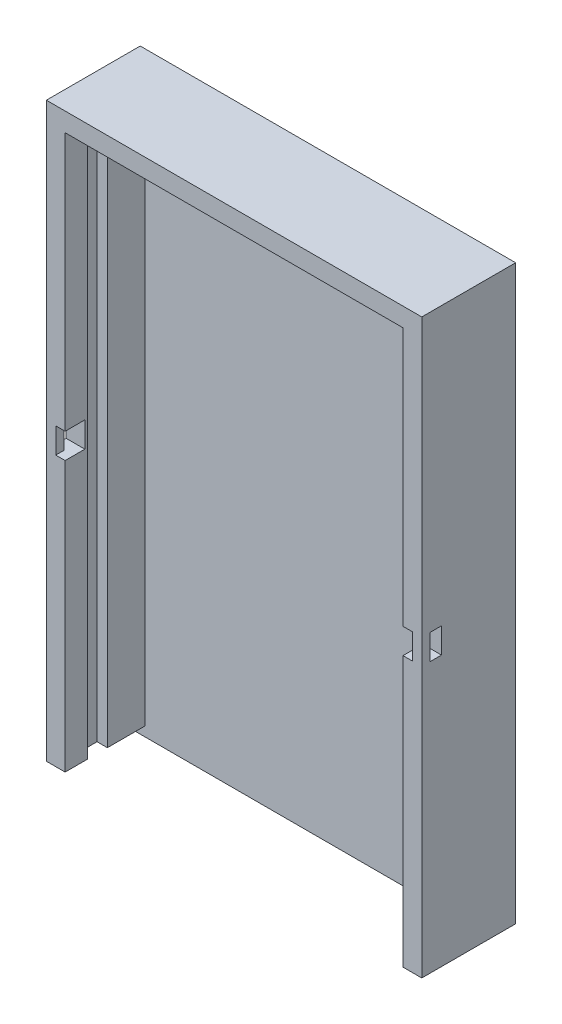
SolidWorks part; units mm, degrees
ref_plane "前视基准面" through (0, 0, 0) normal (0, 0, 1) x (1, 0, 0)
ref_plane "上视基准面" through (0, 0, 0) normal (0, 1, 0) x (1, 0, 0)
ref_plane "右视基准面" through (0, 0, 0) normal (1, 0, 0) x (0, 0, -1)
sketch "草图1" plane through (0, 0, 0) normal (0, 0, 1) x (1, 0, 0)
  line L1 (-20, 31) -> (20, 31)
  line L2 (-20, 31) -> (-20, -31)
  line L3 (-20, -31) -> (20, -31)
  line L4 (20, 31) -> (20, -31)
  line L5 (-20, 31) -> (20, -31) construction
  line L6 (-20, -31) -> (20, 31) construction
  point P0 (0, 0)
  dimension "D1" = 40
  dimension "D2" = 62
extrude "凸台-拉伸1" add sketch "草图1" along normal blind 10 contours L2 L1 L4 L3
sketch "草图2" plane through (0, 0, 10) normal (0, 0, 1) x (1, 0, 0)
  line L12 (18, -29) -> (18, 29)
  line L13 (18, 29) -> (-18, 29)
  line L14 (-18, 29) -> (-18, -29)
  line L15 (-18, -29) -> (18, -29)
  line L16 (18, -29) -> (18, 29)
  line L17 (18, 29) -> (-18, 29)
  line L18 (-18, 29) -> (-18, -29)
  line L19 (-18, -29) -> (18, -29)
  dimension "D1" = 2
extrude "切除-拉伸1" cut sketch "草图2" against normal blind 8.5
sketch "草图4" plane through (0, -31, 0) normal (0, -1, 0) x (1, 0, 0)
  line L0 (-20, 10) -> (20, 10) construction
  line L1 (-18, 10) -> (18, 10)
  line L2 (-18, 10) -> (-18, 1.5)
  line L3 (-18, 1.5) -> (18, 1.5)
  line L4 (18, 10) -> (18, 1.5)
  line L5 (-20, 10) -> (-20, 0) construction
  line L6 (20, 10) -> (20, 0) construction
  line L7 (-20, 0) -> (20, 0) construction
  dimension "D1" = 2
  dimension "D2" = 2
  dimension "D3" = 1.5
extrude "切除-拉伸2" cut sketch "草图4" against normal up to surface (2 mm away) up to face at (0, -29, 5.75)
sketch "草图5" plane through (0, -31, 0) normal (0, -1, 0) x (1, 0, 0)
  line L0 (-18, 1.5) -> (18, 1.5) construction
  line L1 (-19.1, 7.6) -> (19.1, 7.6)
  line L2 (-19.1, 7.6) -> (-19.1, 5.5)
  line L3 (-19.1, 5.5) -> (19.1, 5.5)
  line L4 (19.1, 7.6) -> (19.1, 5.5)
  line L5 (-20, 10) -> (-20, 0) construction
  line L6 (20, 10) -> (20, 0) construction
  dimension "D1" = 4
  dimension "D2" = 2.1
  dimension "D3" = 0.9
  dimension "D4" = 0.9
extrude "切除-拉伸3" cut sketch "草图5" against normal up to surface (60 mm away) up to face at (0, 29, 5.75)
sketch "草图6" plane through (0, -31, 0) normal (0, -1, 0) x (1, 0, 0)
  line L1 (-20, 0) -> (20, 0)
  line L2 (-20, 0) -> (-20, 10)
  line L3 (-20, 10) -> (20, 10)
  line L4 (20, 0) -> (20, 10)
extrude "切除-拉伸4" cut sketch "草图6" against normal blind 1
sketch "草图7" plane through (0, -30, 0) normal (0, -1, 0) x (1, 0, 0)
  line L1 (-19.4, 0) -> (19, 0)
  line L2 (-19.4, 0) -> (-19.4, 1.5)
  line L3 (-19.4, 1.5) -> (19, 1.5)
  line L4 (19, 0) -> (19, 1.5)
  line L5 (20, 0) -> (20, 10) construction
  line L6 (-20, 10) -> (-20, 0) construction
  dimension "D1" = 1.5
  dimension "D2" = 1
  dimension "D3" = 0.6
extrude "凸台-拉伸2" add sketch "草图7" along normal blind 1
sketch "草图8" plane through (-20, 0, 0) normal (-1, 0, 0) x (0, 0, 1)
  line L1 (9.1, 1.45) -> (7.9, 1.45)
  line L2 (9.1, 1.45) -> (9.1, -1.25)
  line L3 (9.1, -1.25) -> (7.9, -1.25)
  line L4 (7.9, 1.45) -> (7.9, -1.25)
  line L5 (10, -30) -> (0, -30) construction
  line L6 (10, 31) -> (10, -30) construction
  dimension "D1" = 28.75
  dimension "D2" = 2.7
  dimension "D3" = 0.9
  dimension "D4" = 1.2
extrude "切除-拉伸5" cut sketch "草图8" against normal through all
sketch "草图10" plane through (-18, 0, 0) normal (1, 0, 0) x (0, 0, -1)
  line L0 (-9.1, -1.25) -> (-9.1, 1.45) construction
  line L1 (-9.1, 1.45) -> (-10, 1.45)
  line L2 (-9.1, 1.45) -> (-9.1, -1.25)
  line L3 (-9.1, -1.25) -> (-10, -1.25)
  line L4 (-10, 1.45) -> (-10, -1.25)
  line L5 (-10, 31) -> (-10, -30) construction
extrude "切除-拉伸6" cut sketch "草图10" against normal blind 1
mirror "镜向1" about plane through (0, 0, 0) normal (1, 0, 0) of "切除-拉伸6"
